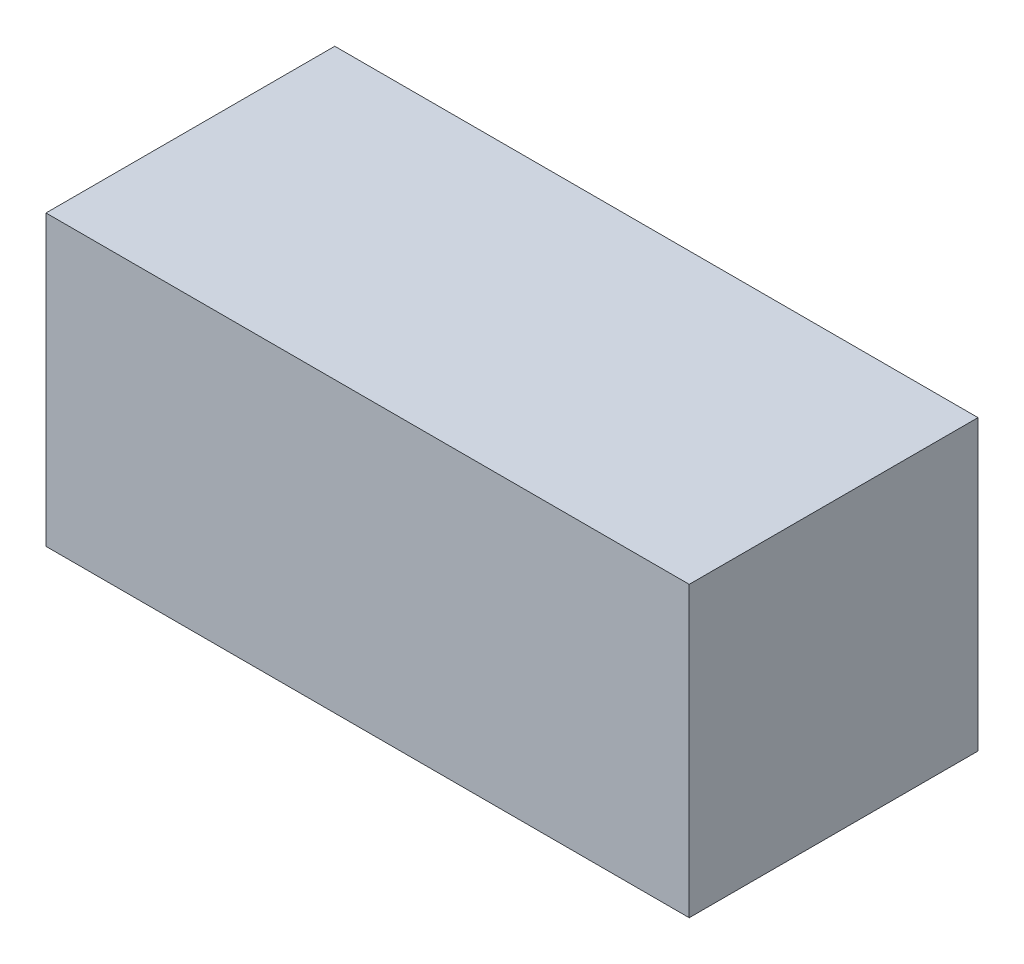
SolidWorks part; units mm, degrees
ref_plane "前视基准面" through (0, 0, 0) normal (0, 0, 1) x (1, 0, 0)
ref_plane "上视基准面" through (0, 0, 0) normal (0, 1, 0) x (1, 0, 0)
ref_plane "右视基准面" through (0, 0, 0) normal (1, 0, 0) x (0, 0, -1)
sketch "草图1" plane through (0, 0, 0) normal (0, 0, 1) x (1, 0, 0)
  line L0 (-1.1125, 0.5) -> (1.115, 0.5)
  line L1 (1.115, 0.5) -> (1.115, -0.5)
  line L2 (1.115, -0.5) -> (-1.1125, -0.5)
  line L3 (-1.1125, -0.5) -> (-1.1125, 0.5)
extrude "Component_Outline" add sketch "草图1" along normal blind 1 separate body
sketch3d "3D草图1"
  line L0 (0, 0, 0) -> (1, 0, 0)
  line L1 (0, 0, 0) -> (0, 1, 0)
  line L2 (0, 0, 0) -> (0, 0, 1)
  point P0 (0, 0, 0)
